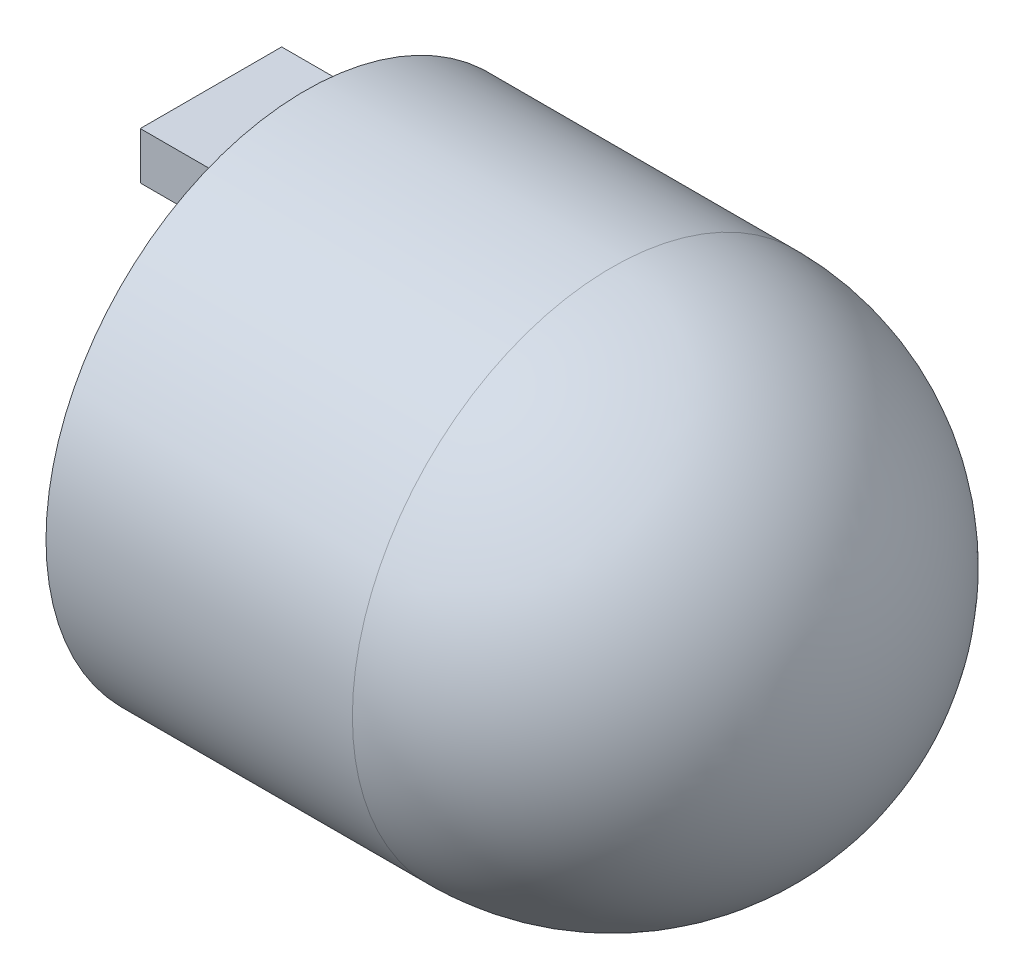
SolidWorks part; units mm, degrees
material "Onyx w/ CF"
ref_plane "Front Plane" through (0, 0, 0) normal (0, 0, 1) x (1, 0, 0)
ref_plane "Top Plane" through (0, 0, 0) normal (0, 1, 0) x (1, 0, 0)
ref_plane "Right Plane" through (0, 0, 0) normal (1, 0, 0) x (0, 0, -1)
sketch "Sketch1" plane through (0, 0, 0) normal (0, 0, 1) x (1, 0, 0)
  line L0 (0, 0) -> (12, 0)
  line L1 (0, 0) -> (0, -5.5)
  line L2 (0, -5.5) -> (6.5, -5.5)
  arc A0 (6.5, -5.5) -> (12, 0) centre (6.5, 0) ccw
  dimension "D1" = 5.5
  dimension "D2" = 12
revolve "Revolve1" add sketch "Sketch1" angle 360 about L0
sketch "Sketch2" plane through (0, 0, 0) normal (-1, 0, 0) x (0, 0, 1)
  line L0 (2.0507, 3.552) -> (-2.0507, 3.552)
  line L1 (1.9774, -3.425) -> (3.9548, 0) construction
  line L2 (3.9548, 0) -> (1.9774, 3.425) construction
  line L3 (1.9774, 3.425) -> (-1.9774, 3.425) construction
  line L4 (-1.9774, 3.425) -> (-3.9548, 0) construction
  line L5 (-3.9548, 0) -> (-1.9774, -3.425) construction
  line L6 (-1.9774, -3.425) -> (1.9774, -3.425) construction
  line L7 (-2.0507, 3.552) -> (-4.1015, 0)
  line L8 (-4.1015, 0) -> (-2.0507, -3.552)
  line L9 (-2.0507, -3.552) -> (2.0507, -3.552)
  line L10 (2.0507, -3.552) -> (4.1015, 0)
  line L11 (4.1015, 0) -> (2.0507, 3.552)
  circle A0 centre (0, 0) radius 3.425 construction
  dimension "D1" = 6.85
  dimension "D2" = 0.127
extrude "Cut-Extrude1" cut sketch "Sketch2" against normal blind 2.75
sketch "Sketch5" plane through (0, 0, 0) normal (-1, 0, 0) x (0, 0, 1)
  line L0 (2.0507, 3.552) -> (-2.0507, 3.552) construction
  line L1 (-1.5, 3.552) -> (1.5, 3.552)
  line L2 (-1.5, 3.552) -> (-1.5, 4.552)
  line L3 (-1.5, 4.552) -> (1.5, 4.552)
  line L4 (1.5, 3.552) -> (1.5, 4.552)
  line L5 (-1.5, -3.552) -> (1.5, -3.552)
  line L6 (-1.5, -3.552) -> (-1.5, -4.552)
  line L7 (-1.5, -4.552) -> (1.5, -4.552)
  line L8 (1.5, -3.552) -> (1.5, -4.552)
  line L9 (2.0507, 3.552) -> (-2.0507, 3.552) construction
  line L10 (-2.0507, -3.552) -> (2.0507, -3.552) construction
  point P16 (0, 3.552)
  dimension "D1" = 1
  dimension "D2" = 3
extrude "Boss-Extrude2" add sketch "Sketch5" along normal blind 2
